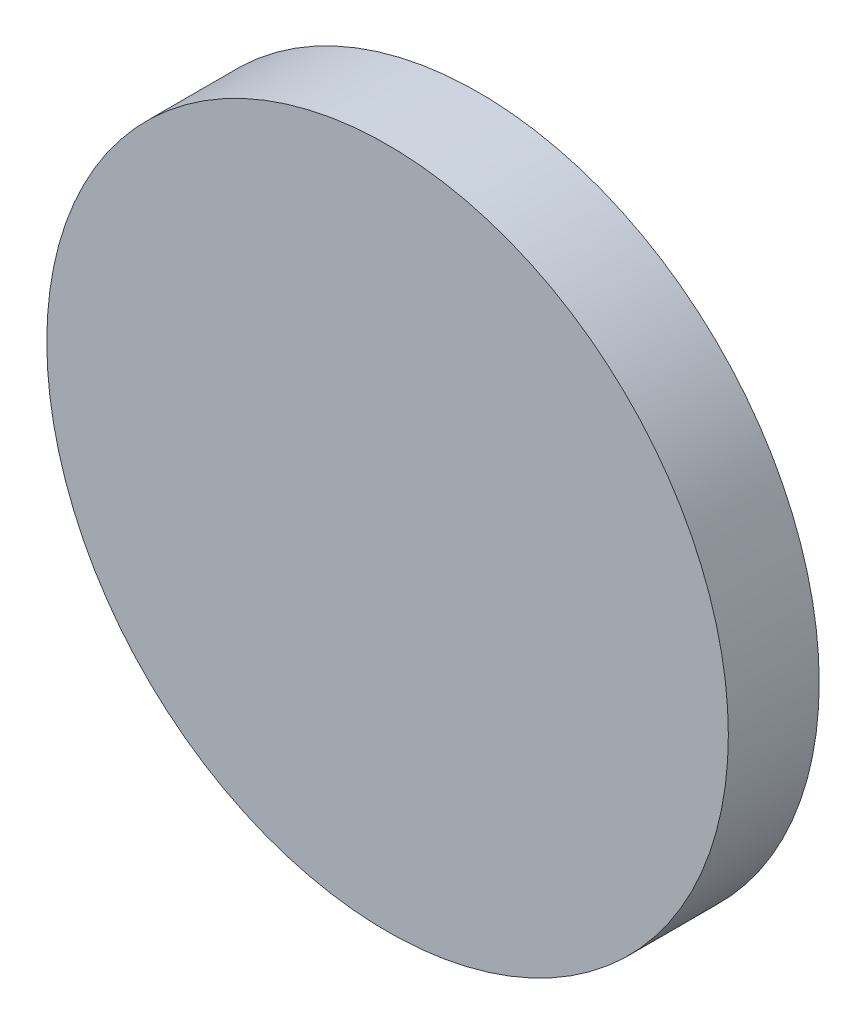
SolidWorks part; units mm, degrees
ref_plane "Front Plane" through (0, 0, 0) normal (0, 0, 1) x (1, 0, 0)
ref_plane "Top Plane" through (0, 0, 0) normal (0, 1, 0) x (1, 0, 0)
ref_plane "Right Plane" through (0, 0, 0) normal (1, 0, 0) x (0, 0, -1)
sketch "Sketch2" plane through (0, 0, 0) normal (0, 0, 1) x (1, 0, 0)
  circle A0 centre (0, 0) radius 75
extrude "Boss-Extrude1" add sketch "Sketch2" along normal blind 20
